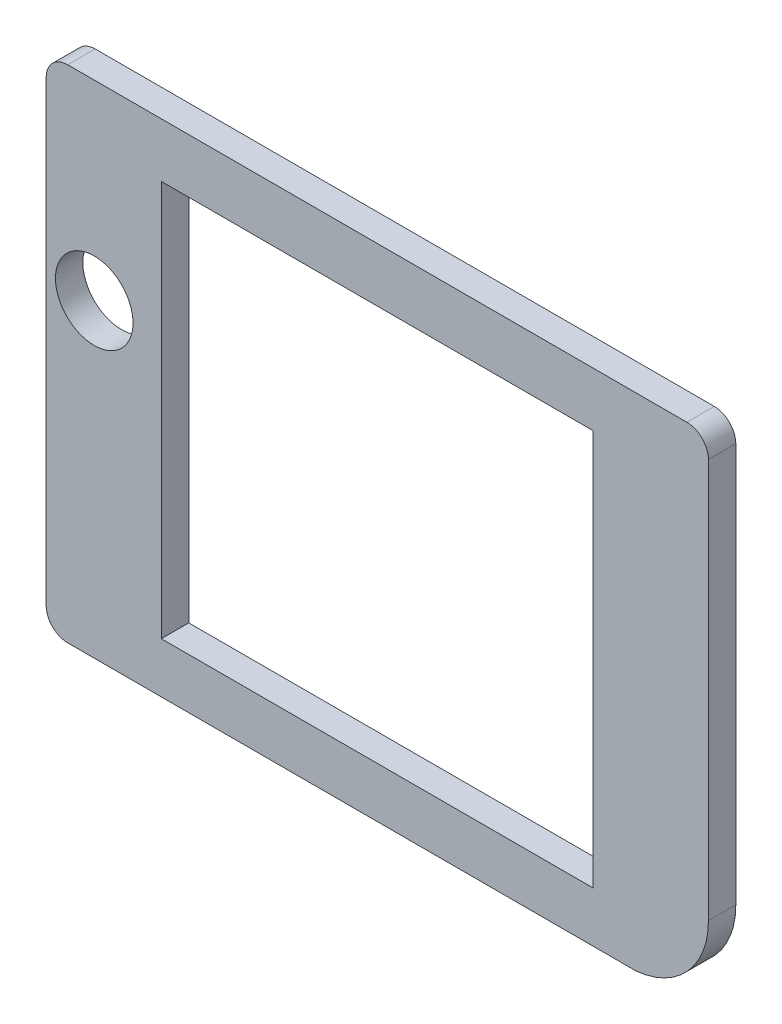
SolidWorks part; units mm, degrees
ref_plane "Front Plane" through (0, 0, 0) normal (0, 0, 1) x (1, 0, 0)
ref_plane "Top Plane" through (0, 0, 0) normal (0, 1, 0) x (1, 0, 0)
ref_plane "Right Plane" through (0, 0, 0) normal (1, 0, 0) x (0, 0, -1)
sketch "Sketch1" plane through (0, 0, 0) normal (0, 0, 1) x (1, 0, 0)
  line L0 (0.1058, 73.6301) -> (-0.0148, 62.4901) construction
  line L1 (-0.0148, 62.4901) -> (-0.0148, 56.2001) construction
  line L2 (-0.0148, 56.2001) -> (-0.0148, 10.268) construction
  line L3 (-15.4692, -49.8142) -> (-8.5409, -45.8142) construction
  line L4 (-15.4692, -49.8142) -> (0.5308, -49.8142) construction
  line L5 (0.5308, -49.8142) -> (7.4591, -45.8142) construction
  line L6 (-0.0148, 10.268) -> (0.1058, -73.6642) construction
  line L15 (-16.3293, -29.1587) -> (-16.3293, -23.8757)
  line L20 (-0.2968, -48.3429) -> (6.6759, -44.4208)
  line L21 (8.2583, -47.1985) -> (1.3584, -51.2855)
  line L22 (-44.5392, 73.6301) -> (44.7508, 73.6301)
  line L23 (44.7508, 73.6301) -> (44.7508, -73.6642)
  line L24 (44.7508, -73.6642) -> (-44.5392, -73.6642)
  line L25 (-44.5392, -73.6642) -> (-44.5392, 73.6301)
  line L26 (-25.0598, 56.2001) -> (-25.0598, 10.268)
  line L27 (-25.0598, 10.268) -> (25.0303, 10.268)
  line L28 (25.0303, 10.268) -> (25.0303, 56.2001)
  line L29 (25.0303, 56.2001) -> (-25.0598, 56.2001)
  line L34 (35.8896, 62.4901) -> (-35.9192, 62.4901)
  line L35 (-38.4192, 59.9901) -> (-38.4192, 6.918)
  line L36 (-35.9192, 4.418) -> (29.9974, 4.418)
  line L37 (38.3896, 13.668) -> (38.3896, 59.9901)
  line L38 (-16.2968, -48.3429) -> (-9.3241, -44.4208)
  line L39 (-7.7417, -47.1985) -> (-14.6416, -51.2855)
  line L150 (42.2525, -55.0539) -> (42.2511, -54.9499)
  circle A2 centre (-26.9008, -26.5172) radius 3.6
  arc A3 (8.2583, -47.1985) -> (6.6759, -44.4208) centre (7.4591, -45.8142) ccw
  arc A6 (-16.2968, -48.3429) -> (-14.6416, -51.2855) centre (-15.4692, -49.8142) ccw
  arc A7 (-7.7417, -47.1985) -> (-9.3241, -44.4208) centre (-8.5409, -45.8142) ccw
  circle A15 centre (18.9576, -29.5613) radius 3.5
  circle A16 centre (33.0683, -21.4917) radius 3.5
  arc A17 (-0.2968, -48.3429) -> (1.3584, -51.2855) centre (0.5308, -49.8142) ccw
  circle A19 centre (-32.8459, 40.326) radius 4.5
  arc A24 (38.3896, 59.9901) -> (35.8896, 62.4901) centre (35.8896, 59.9901) ccw
  arc A25 (-35.9192, 62.4901) -> (-38.4192, 59.9901) centre (-35.9192, 59.9901) ccw
  arc A26 (-38.4192, 6.918) -> (-35.9192, 4.418) centre (-35.9192, 6.918) ccw
  arc A27 (29.9974, 4.418) -> (38.3896, 13.668) centre (29.1397, 13.6282) ccw
  dimension "D4" = 11.14
  dimension "D8" = 7
  dimension "D11" = 9
  dimension "D12" = 7.2
  dimension "D14" = 9.25
  dimension "D15" = 2.5
  dimension "D2" = 89.29
  dimension "D3" = 147.2943
  dimension "D5" = 25.9097
  dimension "D6" = 8.0696
  dimension "D7" = 14.1107
  dimension "D9" = 7.7861
  dimension "D10" = 22.1641
  dimension "D13" = 10.5715
  dimension "D16" = 6.29
  dimension "D17" = 6.12
  dimension "D18" = 5.85
  dimension "D19" = 16
  dimension "D20" = 8
  dimension "D21" = 29.07
  dimension "D22" = 23.85
  dimension "D23" = 30
extrude "Bezel" add sketch "Sketch1" along normal blind 3.18 contours L36 A27 L37 A24 L34 A25 L35 A26 L29 L28 L27 L26 A19
